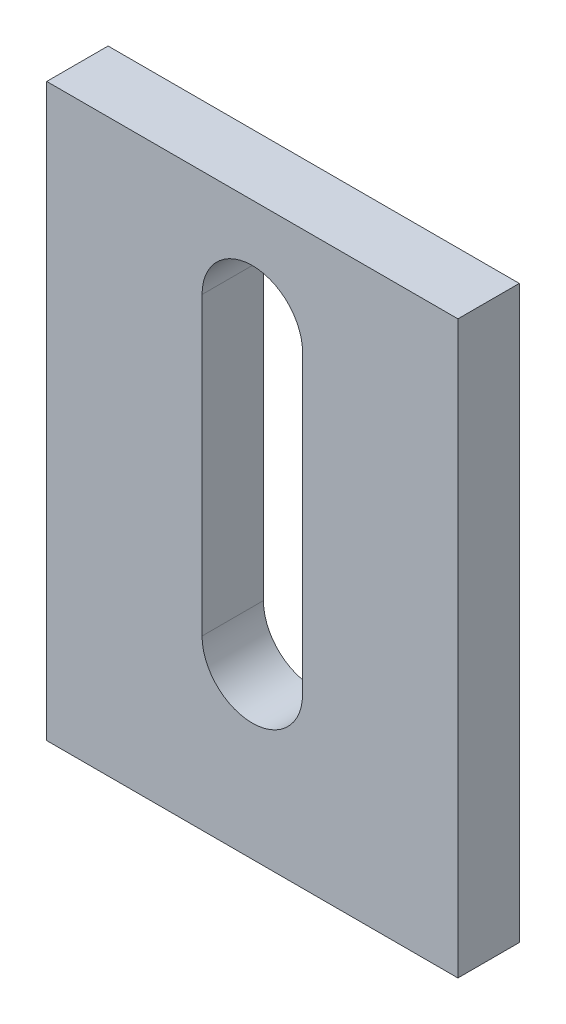
SolidWorks part; units mm, degrees
ref_plane "前视基准面" through (0, 0, 0) normal (0, 0, 1) x (1, 0, 0)
ref_plane "上视基准面" through (0, 0, 0) normal (0, 1, 0) x (1, 0, 0)
ref_plane "右视基准面" through (0, 0, 0) normal (1, 0, 0) x (0, 0, -1)
sketch "草图1" plane through (0, 0, 0) normal (0, 0, 1) x (1, 0, 0)
  line L0 (0, 0) -> (3, 0)
  line L1 (0, 0) -> (35, 0) construction
  line L2 (0, 0) -> (0, -40) construction
  line L3 (0, -40) -> (35, -40) construction
  line L4 (35, 0) -> (35, -40) construction
  line L5 (35, 0) -> (32, 0)
  line L6 (0, -40) -> (0, -35.7)
  line L7 (0, -35.7) -> (63.6248, -35.7) construction
  line L8 (31.8124, -35.7) -> (31.8124, -40)
  line L9 (3, 0) -> (31.8124, 0)
  line L10 (3, 0) -> (3, -35.7)
  line L11 (3, -35.7) -> (31.8124, -35.7) construction
  line L12 (31.8124, 0) -> (31.8124, -35.7)
  line L13 (17.4062, -7.4876) -> (17.4062, -28.2124) construction
  line L14 (20.9284, -7.4876) -> (20.9284, -28.2124)
  line L15 (13.884, -7.4876) -> (13.884, -28.2124)
  line L16 (31.8124, -40) -> (3, -40)
  line L17 (3, -40) -> (3, -35.7)
  arc A0 (20.9284, -7.4876) -> (13.884, -7.4876) centre (17.4062, -7.4876) ccw
  arc A1 (13.884, -28.2124) -> (20.9284, -28.2124) centre (17.4062, -28.2124) ccw
  point P14 (17.4062, -17.85)
extrude "凸台-拉伸1" add sketch "草图1" along normal blind 4.3 contours L12 L9 L10 L11 A1 L15 A0 L14
